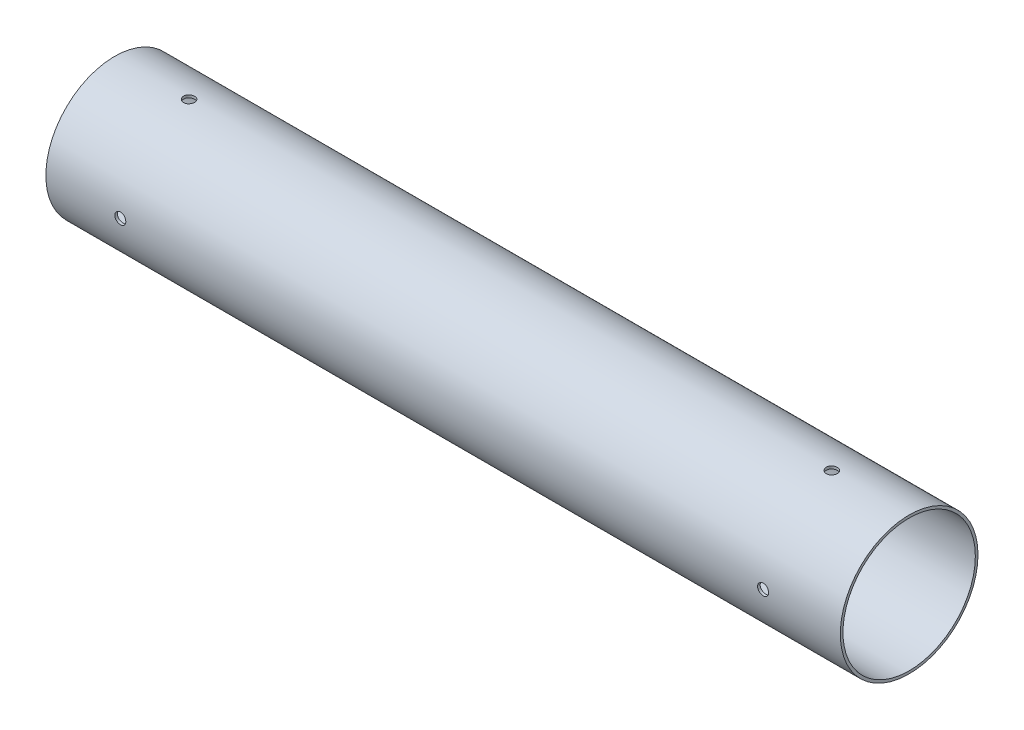
SolidWorks part; units mm, degrees
ref_plane "Front Plane" through (0, 0, 0) normal (1, 0, 0) x (0, 1, 0)
ref_plane "Top Plane" through (0, 0, 0) normal (0, 0, 1) x (0, 1, 0)
ref_plane "Right Plane" through (0, 0, 0) normal (0, 1, 0) x (-1, 0, 0)
sketch "Sketch1" plane through (0, 0, 0) normal (1, 0, 0) x (0, 1, 0)
  circle A0 centre (0, 0) radius 39.624
  circle A1 centre (0, 0) radius 38.1
  dimension "D1" = 79.248
  dimension "D2" = 76.2
extrude "Boss-Extrude1" add sketch "Sketch1" along normal blind 457.2
sketch "Sketch2" plane through (0, 0, 0) normal (0, 1, 0) x (-1, 0, 0)
  circle A0 centre (-42.8244, 0) radius 3.175
  dimension "D1" = 6.35
  dimension "D2" = 42.8244
extrude "Cut-Extrude1" cut sketch "Sketch2" along normal through all
pattern_circular "CirPattern1" count 4 over 360 about axis through (457.2, 0, 0) along (-1, 0, 0) of "Cut-Extrude1"
sketch "Sketch3" plane through (0, 0, 0) normal (0, 1, 0) x (-1, 0, 0)
  line L0 (-457.2, 39.624) -> (-457.2, -39.624) construction
  circle A0 centre (-412.75, 0) radius 3.175
  dimension "D2" = 6.35
  dimension "D1" = 44.45
extrude "Cut-Extrude2" cut sketch "Sketch3" along normal through all
pattern_circular "CirPattern2" count 4 over 360 about axis through (457.2, 0, 0) along (-1, 0, 0) of "Cut-Extrude2"
